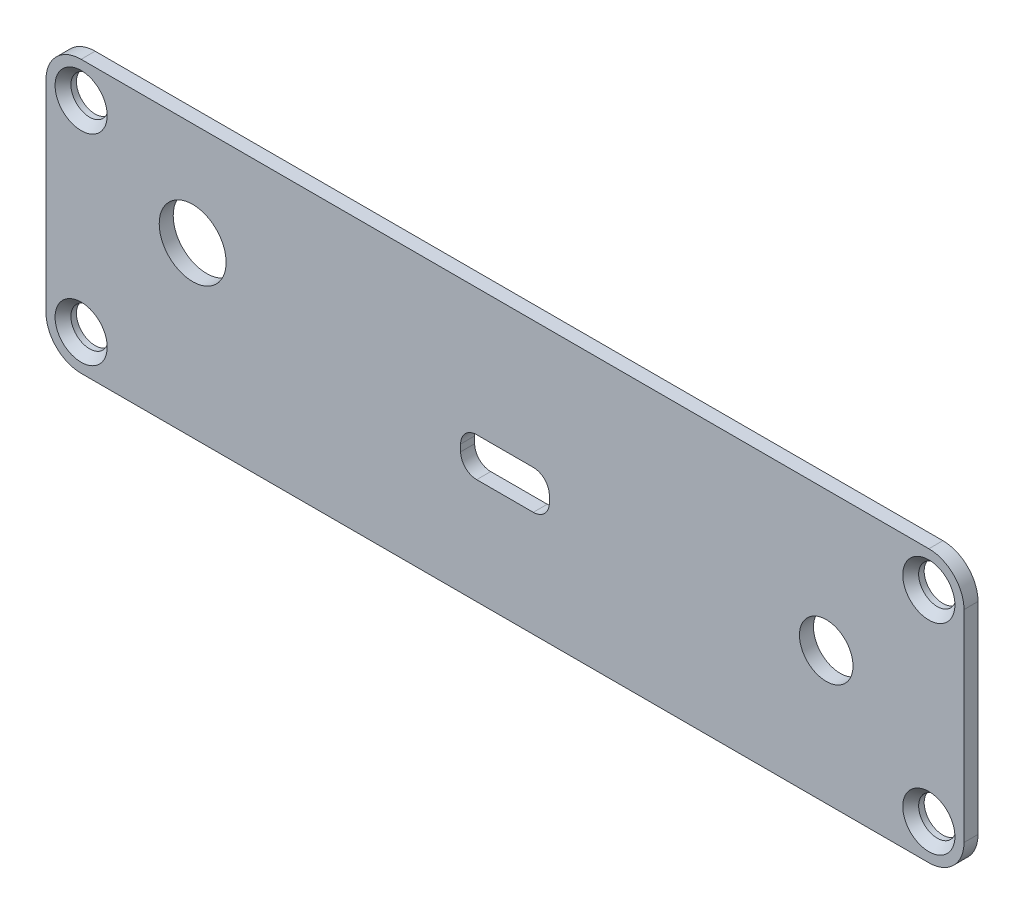
SolidWorks part; units mm, degrees
ref_plane "Front Plane" through (0, 0, 0) normal (0, 0, 1) x (1, 0, 0)
ref_plane "Top Plane" through (0, 0, 0) normal (0, 1, 0) x (1, 0, 0)
ref_plane "Right Plane" through (0, 0, 0) normal (1, 0, 0) x (0, 0, -1)
sketch "Sketch1" plane through (0, 0, 0) normal (0, 0, 1) x (1, 0, 0)
  line L1 (0, 0) -> (102.87, 0)
  line L2 (0, 0) -> (0, 30.48)
  line L3 (0, 30.48) -> (102.87, 30.48)
  line L4 (102.87, 0) -> (102.87, 30.48)
  dimension "D1" = 102.87
  dimension "D2" = 30.48
extrude "Boss-Extrude1" add sketch "Sketch1" along normal blind 1.57
fillet "Fillet1" radius 3.935 4 edges at (0, 0, 0.785) (102.87, 0, 0.785) (102.87, 30.48, 0.785) (0, 30.48, 0.785)
hole_wizard "CSK for #6 Flat Head Machine Screw1" positions "Sketch3" profile "Sketch4" countersink size "#6" standard "ANSI Inch" end condition through all
sketch "Sketch3" plane through (0, 0, 1.57) normal (0, 0, 1) x (1, 0, 0)
  line L0 (0, 26.545) -> (0, 3.935) construction
  line L1 (98.935, 30.48) -> (3.935, 30.48) construction
  line L2 (3.935, 0) -> (98.935, 0) construction
  line L3 (102.87, 3.935) -> (102.87, 26.545) construction
  point P0 (3.937, 26.4795)
  point P8 (3.937, 4.0005)
  point P10 (98.933, 26.4795)
  point P12 (98.933, 4.0005)
  dimension "D1" = 3.937
  dimension "D2" = 4.0005
  dimension "D3" = 3.937
  dimension "D4" = 4.0005
  dimension "D5" = 3.937
  dimension "D6" = 4.0005
  dimension "D7" = 4.0005
  dimension "D8" = 3.937
sketch "Sketch4" plane through (3.937, 26.4795, 1.57) normal (1, 0, 0) x (0, -1, 0)
  line L0 (0, 0) -> (0, 1.57)
  line L1 (0, 1.57) -> (2.0955, 1.57)
  line L2 (2.0955, 1.57) -> (2.0955, 0.9496)
  line L3 (2.0955, 0.9496) -> (2.921, 0)
  line L5 (2.921, 0) -> (0, 0)
  line L6 (-2.0955, 0.9496) -> (-2.921, 0) construction
  line L11 (0, -6.35) -> (0, 107.95) construction
  dimension "Thru Hole Dia." = 4.191
  dimension "Thru Hole Depth" = 1.57
  dimension "Near C'Sink Dia." = 5.842
  dimension "Near C'Sink Angle" = 82
sketch "data side" plane through (0, 0, 0) normal (0, 0, 1) x (1, 0, 0)
  line L0 (1.435, 10.7795) -> (0, 10.7795) construction
  line L1 (1.435, 10.7795) -> (101.435, 10.7795) construction
  line L2 (1.435, 10.7795) -> (1.435, 12.3495) construction
  line L3 (1.435, 12.3495) -> (101.435, 12.3495) construction
  line L4 (101.435, 10.7795) -> (101.435, 12.3495) construction
  line L6 (101.435, 10.7795) -> (102.87, 10.7795) construction
  line L8 (102.87, 3.935) -> (102.87, 26.545) construction
  line L21 (0, 26.545) -> (0, 3.935) construction
  line L22 (3.935, 0) -> (98.935, 0) construction
  line L23 (46.965, 14.0295) -> (55.905, 14.0295) construction
  line L24 (48.265, 15.7095) -> (54.605, 15.7095)
  line L25 (46.965, 14.4095) -> (46.965, 13.6495)
  line L26 (48.265, 12.3495) -> (54.605, 12.3495)
  line L27 (55.905, 14.4095) -> (55.905, 13.6495)
  line L28 (51.435, 12.3495) -> (51.435, 15.7095) construction
  line L29 (46.965, 15.7095) -> (0, 15.7095) construction
  line L30 (55.905, 15.7095) -> (102.87, 15.7095) construction
  arc A1 (54.605, 12.3495) -> (55.905, 13.6495) centre (54.605, 13.6495) ccw
  arc A2 (54.605, 15.7095) -> (55.905, 14.4095) centre (54.605, 14.4095) cw
  arc A3 (46.965, 13.6495) -> (48.265, 12.3495) centre (48.265, 13.6495) ccw
  arc A4 (48.265, 15.7095) -> (46.965, 14.4095) centre (48.265, 14.4095) ccw
  circle A5 centre (16.435, 18.8995) radius 3.25
  circle A6 centre (87.435, 14.8495) radius 2.5
  point P32 (46.965, 12.3495)
  dimension "D4" = 5
  dimension "D5" = 2.5
  dimension "D6" = 6.5
  dimension "D10" = 1.3
  dimension "D13" = 14
  dimension "D2" = 1.57
  dimension "D3" = 100
  dimension "D7" = 8.94
  dimension "D8" = 3.36
  dimension "D11" = 6.55
  dimension "D12" = 15
  dimension "D14" = 10.7795
sketch "io side" [suppressed] plane through (0, 0, 1.57) normal (0, 0, 1) x (1, 0, 0)
  line L0 (1.435, 10.7795) -> (0, 10.7795) construction
  line L1 (1.435, 10.7795) -> (101.435, 10.7795) construction
  line L2 (1.435, 10.7795) -> (1.435, 12.3495) construction
  line L3 (1.435, 12.3495) -> (101.435, 12.3495) construction
  line L4 (101.435, 10.7795) -> (101.435, 12.3495) construction
  line L5 (0, 26.545) -> (0, 3.935) construction
  line L6 (101.435, 10.7795) -> (102.87, 10.7795) construction
  line L7 (102.87, 3.935) -> (102.87, 26.545) construction
  line L9 (75.385, 19.8995) -> (83.785, 19.8995)
  line L10 (75.385, 19.8995) -> (75.385, 12.3495)
  line L11 (75.385, 12.3495) -> (83.785, 12.3495)
  line L12 (83.785, 19.8995) -> (83.785, 12.3495)
  line L13 (43.79, 19.8995) -> (59.19, 19.8995)
  line L14 (43.79, 19.8995) -> (43.79, 12.3495)
  line L15 (43.79, 12.3495) -> (59.19, 12.3495)
  line L16 (59.19, 19.8995) -> (59.19, 12.3495)
  line L17 (9.985, 12.3495) -> (28.885, 12.3495)
  line L18 (9.985, 12.3495) -> (9.985, 19.8995)
  line L19 (9.985, 19.8995) -> (28.885, 19.8995)
  line L20 (28.885, 12.3495) -> (28.885, 19.8995)
  circle A0 centre (89.8563, 16.7478) radius 2.15
  dimension "D4" = 4.3983
  dimension "D5" = 11.5787
  dimension "D6" = 4.3
  dimension "D1" = 10.7795
  dimension "D2" = 1.57
  dimension "D3" = 100
  dimension "D7" = 8.4
  dimension "D8" = 7.55
  dimension "D9" = 17.65
  dimension "D10" = 15.4
  dimension "D11" = 18.9
  dimension "D12" = 42.245
  dimension "D13" = 72.55
sketch "Sketch6" [suppressed] plane through (0, 0, 1.57) normal (0, 0, 1) x (1, 0, 0)
  line L0 (75.385, 19.8995) -> (75.385, 12.3495) construction
  line L1 (75.385, 12.3495) -> (83.785, 12.3495) construction
  line L2 (83.785, 19.8995) -> (83.785, 12.3495) construction
  line L3 (75.385, 19.8995) -> (83.785, 19.8995) construction
  line L4 (59.19, 19.8995) -> (59.19, 12.3495) construction
  line L5 (43.79, 12.3495) -> (59.19, 12.3495) construction
  line L6 (43.79, 19.8995) -> (43.79, 12.3495) construction
  line L7 (43.79, 19.8995) -> (59.19, 19.8995) construction
  line L8 (9.985, 12.3495) -> (9.985, 19.8995) construction
  line L9 (9.985, 12.3495) -> (28.885, 12.3495) construction
  line L10 (28.885, 12.3495) -> (28.885, 19.8995) construction
  line L11 (9.985, 19.8995) -> (28.885, 19.8995) construction
  line L12 (75.385, 19.8995) -> (75.385, 12.3495)
  line L13 (75.385, 12.3495) -> (83.785, 12.3495)
  line L14 (83.785, 19.8995) -> (83.785, 12.3495)
  line L15 (75.385, 19.8995) -> (83.785, 19.8995)
  line L16 (59.19, 19.8995) -> (59.19, 12.3495)
  line L17 (43.79, 12.3495) -> (59.19, 12.3495)
  line L18 (43.79, 19.8995) -> (43.79, 12.3495)
  line L19 (43.79, 19.8995) -> (59.19, 19.8995)
  line L20 (9.985, 12.3495) -> (9.985, 19.8995)
  line L21 (9.985, 12.3495) -> (28.885, 12.3495)
  line L22 (28.885, 12.3495) -> (28.885, 19.8995)
  line L23 (9.985, 19.8995) -> (28.885, 19.8995)
  circle A0 centre (89.8563, 16.7478) radius 2.15 construction
  circle A1 centre (89.8563, 16.7478) radius 2.15
extrude "Cut-Extrude1" [suppressed] cut sketch "Sketch6" against normal through all
other "Move Face1" [suppressed] parameters "D1"=0.4
extrude "Cut-Extrude9" cut sketch "data side" along normal up to surface (1.57 mm away) up to face at (6.858, 26.4795, 1.57)
other "Move Face4" face at (84.935, 14.8495, 1.57) face at (13.185, 18.8995, 1.57) face at (55.3896, 12.8649, 0.785) face at (55.3896, 15.1941, 0.785) face at (55.905, 14.0295, 0.785) face at (51.435, 12.3495, 0.785) face at (47.4804, 12.8649, 0.785) face at (46.965, 14.0295, 0.785) face at (51.435, 15.7095, 0.785) face at (47.4804, 15.1941, 0.785) parameters "D1"=0.5
equation "\"D3@Sketch3\"=\"D1@Sketch3\""
equation "\"D4@Sketch3\"=\"D2@Sketch3\""
equation "\"D5@Sketch3\"=\"D1@Sketch3\""
equation "\"D6@Sketch3\"=\"D2@Sketch3\""
equation "\"D7@Sketch3\"=\"D2@Sketch3\""
equation "\"D8@Sketch3\"=\"D1@Sketch3\""
